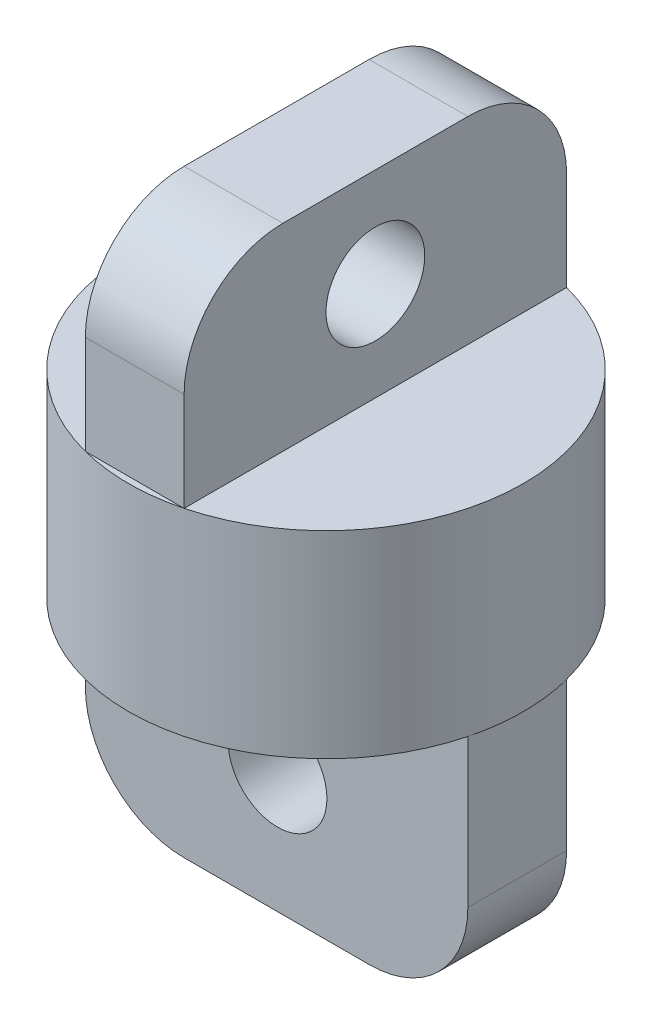
SolidWorks part; units mm, degrees
ref_plane "Front Plane" through (0, 0, 0) normal (0, 0, 1) x (1, 0, 0)
ref_plane "Top Plane" through (0, 0, 0) normal (0, 1, 0) x (1, 0, 0)
ref_plane "Right Plane" through (0, 0, 0) normal (1, 0, 0) x (0, 0, -1)
sketch "Sketch1" plane through (0, 0, 0) normal (0, 1, 0) x (1, 0, 0)
  circle A0 centre (0, 0) radius 50.8
  dimension "D1" = 101.6
extrude "Boss-Extrude1" add sketch "Sketch1" along normal blind 50.8
sketch "Sketch3" plane through (0, 0, 0) normal (0, -1, 0) x (1, 0, 0)
  line L1 (-49.1869, -12.7) -> (49.1869, -12.7)
  line L2 (-49.1869, -12.7) -> (-49.1869, 12.7)
  line L3 (-49.1869, 12.7) -> (49.1869, 12.7)
  line L4 (49.1869, -12.7) -> (49.1869, 12.7)
  line L5 (-49.1869, -12.7) -> (49.1869, 12.7) construction
  line L6 (-49.1869, 12.7) -> (49.1869, -12.7) construction
  circle A0 centre (0, 0) radius 50.8 construction
  point P0 (0, 0)
  dimension "D1" = 25.4
extrude "Boss-Extrude3" add sketch "Sketch3" along normal blind 63.5
sketch "Sketch4" plane through (0, 0, 12.7) normal (0, 0, 1) x (1, 0, 0)
  circle A0 centre (0.244, -31.9671) radius 12.7
extrude "Cut-Extrude1" cut sketch "Sketch4" against normal through all contours A0
fillet "Fillet1" radius 25.4 1 edges at (-49.1869, -63.5, 0)
fillet "Fillet2" radius 25.4 1 edges at (49.1869, -63.5, 0)
sketch "Sketch5" plane through (0, 50.8, 0) normal (0, 1, 0) x (1, 0, 0)
  line L1 (-12.7, -49.1869) -> (12.7, -49.1869)
  line L2 (-12.7, -49.1869) -> (-12.7, 49.1869)
  line L3 (-12.7, 49.1869) -> (12.7, 49.1869)
  line L4 (12.7, -49.1869) -> (12.7, 49.1869)
  line L5 (-12.7, -49.1869) -> (12.7, 49.1869) construction
  line L6 (-12.7, 49.1869) -> (12.7, -49.1869) construction
  circle A0 centre (0, 0) radius 50.8 construction
  point P1 (0, 0)
  dimension "D1" = 25.4
extrude "Boss-Extrude4" add sketch "Sketch5" along normal blind 50.8
sketch "Sketch6" plane through (12.7, 0, 0) normal (1, 0, 0) x (0, 0, -1)
  circle A0 centre (0, 76.2) radius 12.7
extrude "Cut-Extrude2" cut sketch "Sketch6" against normal blind 50.8 contours A0
fillet "Fillet3" radius 25.4 2 edges at (0, 101.6, 49.1869) (0, 101.6, -49.1869)
